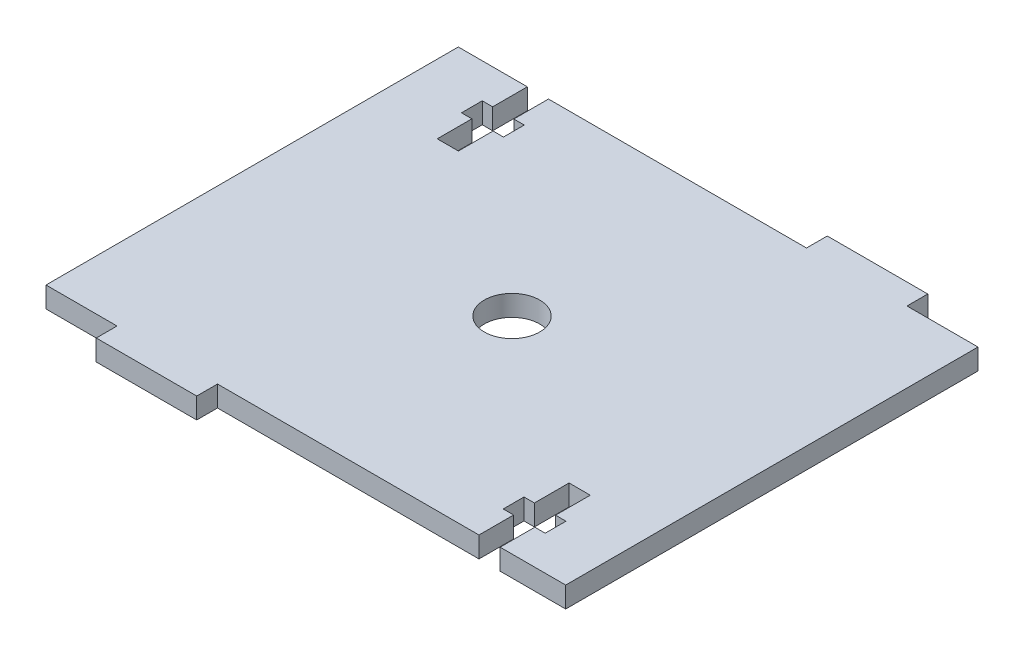
SolidWorks part; units mm, degrees
ref_plane "Plan de face" through (0, 0, 0) normal (0, 0, 1) x (1, 0, 0)
ref_plane "Plan de dessus" through (0, 0, 0) normal (0, 1, 0) x (1, 0, 0)
ref_plane "Plan de droite" through (0, 0, 0) normal (1, 0, 0) x (0, 0, -1)
sketch "Esquisse3" plane through (0, 0, 0) normal (0, 1, 0) x (1, 0, 0)
  line L0 (37.5, 87.5665) -> (37.5, -36.5027) construction
  line L1 (0, 0) -> (75, 0)
  line L2 (0, 0) -> (0, 59.5)
  line L3 (0, 59.5) -> (75, 59.5)
  line L4 (75, 0) -> (75, 59.5)
  line L5 (-41.8883, 29.75) -> (157.9787, 29.75) construction
  line L6 (24.75, 0) -> (24.75, -3)
  line L7 (50.25, 59.5) -> (64.75, 59.5)
  line L8 (50.25, 59.5) -> (50.25, 62.5)
  line L9 (50.25, 62.5) -> (64.75, 62.5)
  line L10 (64.75, 59.5) -> (64.75, 62.5)
  line L11 (24.75, -3) -> (10.25, -3)
  line L12 (10.25, 0) -> (10.25, -3)
  line L13 (10.25, 0) -> (24.75, 0)
  line L14 (65.5416, 5) -> (67.0416, 5)
  line L15 (67.0416, 5) -> (67.0416, 8)
  line L16 (67.0416, 8) -> (65.5416, 8)
  line L17 (65.5416, 8) -> (65.5416, 13)
  line L18 (65.5416, 13) -> (62.4841, 13)
  line L19 (62.4841, 13) -> (62.4841, 8)
  line L20 (62.4841, 8) -> (60.9841, 8)
  line L21 (60.9841, 8) -> (60.9841, 5)
  line L22 (9.9584, 59.5) -> (9.9584, 54.5)
  line L23 (9.9584, 54.5) -> (8.4584, 54.5)
  line L24 (8.4584, 54.5) -> (8.4584, 51.5)
  line L25 (8.4584, 51.5) -> (9.9584, 51.5)
  line L26 (9.9584, 51.5) -> (9.9584, 46.5)
  line L27 (9.9584, 46.5) -> (13.0159, 46.5)
  line L28 (13.0159, 46.5) -> (13.0159, 51.5)
  line L29 (13.0159, 51.5) -> (14.5159, 51.5)
  line L30 (14.5159, 51.5) -> (14.5159, 54.5)
  line L31 (14.5159, 54.5) -> (13.0159, 54.5)
  line L32 (13.0159, 54.5) -> (13.0159, 59.5)
  line L33 (13.0159, 59.5) -> (9.9584, 59.5)
  line L34 (60.9841, 5) -> (62.4841, 5)
  line L35 (62.4841, 5) -> (62.4841, 0)
  line L36 (65.5416, 5) -> (65.5416, 0)
  line L37 (65.5416, 0) -> (62.4841, 0)
  circle A0 centre (37.5, 29.75) radius 4
  point P5 (0, 29.75)
  point P6 (37.5, 59.5)
  point P24 (37.5, 29.75)
  point P47 (37.75, 29.75)
  dimension "D3" = 8
  dimension "D1" = 75
  dimension "D2" = 59.5
  dimension "D4" = 2
  dimension "D5" = 2
  dimension "D7" = 14.5
  dimension "D8" = 3
  dimension "D9" = 10.25
  dimension "D10" = 3
  dimension "D11" = 5
  dimension "D12" = 5
  dimension "D13" = 1.5
extrude "Boss.-Extru.1" add sketch "Esquisse3" along normal blind 3 contours L1 L12 L11 L6 | L14 L36 L1 L4 L3 L32 L31 L30 L29 L28 L27 L26 L25 L24 L23 L22 L2 L35 L34 L21 L20 L19 L18 L17 L16 L15 A0 | L3 L10 L9 L8
